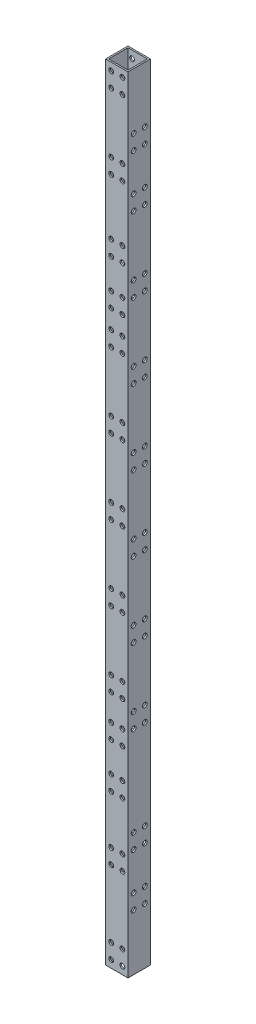
SolidWorks part; units mm, degrees
ref_plane "前视基准面" through (0, 0, 0) normal (0, 0, 1) x (1, 0, 0)
ref_plane "上视基准面" through (0, 0, 0) normal (0, 1, 0) x (1, 0, 0)
ref_plane "右视基准面" through (0, 0, 0) normal (1, 0, 0) x (0, 0, -1)
other "Configuration Table"
sketch "草图1" plane through (0, 0, 0) normal (0, 1, 0) x (1, 0, 0)
  line L1 (6.5, -6.5) -> (-6.5, -6.5)
  line L2 (6.5, -6.5) -> (6.5, 6.5)
  line L3 (6.5, 6.5) -> (-6.5, 6.5)
  line L4 (-6.5, -6.5) -> (-6.5, 6.5)
  line L5 (6.5, -6.5) -> (-6.5, 6.5) construction
  line L6 (6.5, 6.5) -> (-6.5, -6.5) construction
  line L7 (7.5, -7.5) -> (-7.5, -7.5)
  line L8 (7.5, -7.5) -> (7.5, 7.5)
  line L9 (7.5, 7.5) -> (-7.5, 7.5)
  line L10 (-7.5, -7.5) -> (-7.5, 7.5)
  line L11 (7.5, -7.5) -> (-7.5, 7.5) construction
  line L12 (7.5, 7.5) -> (-7.5, -7.5) construction
  point P0 (0, 0)
  point P6 (0, 0)
  dimension "D1" = 15
  dimension "D2" = 13
extrude "凸台-拉伸1" add sketch "草图1" along normal blind 525
sketch "草图2" plane through (0, 0, 7.5) normal (0, 0, 1) x (1, 0, 0)
  line L0 (0, 804.3358) -> (0, 762.8538) construction
  line L1 (-7.5, 465) -> (7.5, 465) construction
  line L2 (-7.5, 525) -> (-7.5, 0) construction
  line L3 (7.5, 525) -> (7.5, 0) construction
  line L4 (-7.5, 525) -> (7.5, 525) construction
  line L5 (-7.5, 262.5) -> (7.5, 262.5) construction
  line L6 (-7.5, 402.5) -> (7.5, 402.5) construction
  line L7 (-7.5, 515) -> (7.5, 515) construction
  line L8 (-7.5, 10) -> (7.5, 10) construction
  line L9 (-7.5, 417.5) -> (7.5, 417.5) construction
  line L10 (-7.5, 387.5) -> (7.5, 387.5) construction
  line L11 (-7.5, 137.5) -> (7.5, 137.5) construction
  line L12 (-7.5, 107.5) -> (7.5, 107.5) construction
  line L13 (-7.5, 122.5) -> (7.5, 122.5) construction
  circle A9 centre (3.75, 520) radius 1.6
  circle A11 centre (-3.75, 520) radius 1.6
  circle A12 centre (-3.75, 510) radius 1.6
  circle A13 centre (3.75, 510) radius 1.6
  circle A14 centre (3.75, 15) radius 1.6
  circle A15 centre (-3.75, 15) radius 1.6
  circle A16 centre (-3.75, 5) radius 1.6
  circle A17 centre (3.75, 5) radius 1.6
  circle A18 centre (-3.75, 470) radius 1.6
  circle A19 centre (3.75, 470) radius 1.6
  circle A20 centre (3.75, 460) radius 1.6
  circle A21 centre (-3.75, 460) radius 1.6
  circle A26 centre (-3.75, 370) radius 1.6
  circle A27 centre (3.75, 370) radius 1.6
  circle A28 centre (3.75, 360) radius 1.6
  circle A29 centre (-3.75, 360) radius 1.6
  circle A30 centre (-3.75, 320) radius 1.6
  circle A31 centre (3.75, 320) radius 1.6
  circle A32 centre (3.75, 310) radius 1.6
  circle A33 centre (-3.75, 310) radius 1.6
  circle A34 centre (-3.75, 270) radius 1.6
  circle A35 centre (3.75, 270) radius 1.6
  circle A36 centre (3.75, 260) radius 1.6
  circle A37 centre (-3.75, 260) radius 1.6
  circle A38 centre (-3.75, 220) radius 1.6
  circle A39 centre (3.75, 220) radius 1.6
  circle A40 centre (3.75, 210) radius 1.6
  circle A41 centre (-3.75, 210) radius 1.6
  circle A42 centre (-3.75, 170) radius 1.6
  circle A43 centre (3.75, 170) radius 1.6
  circle A44 centre (3.75, 160) radius 1.6
  circle A45 centre (-3.75, 160) radius 1.6
  circle A50 centre (-3.75, 70) radius 1.6
  circle A51 centre (3.75, 70) radius 1.6
  circle A52 centre (3.75, 60) radius 1.6
  circle A53 centre (-3.75, 60) radius 1.6
  circle A54 centre (-3.75, 420) radius 1.6 [skipped]
  circle A55 centre (3.75, 420) radius 1.6 [skipped]
  circle A56 centre (-3.75, 410) radius 1.6 [skipped]
  circle A57 centre (3.75, 410) radius 1.6 [skipped]
  circle A58 centre (-3.75, 422.5) radius 1.6
  circle A59 centre (3.75, 422.5) radius 1.6
  circle A60 centre (3.75, 412.5) radius 1.6
  circle A61 centre (-3.75, 412.5) radius 1.6
  circle A62 centre (-3.75, 392.5) radius 1.6
  circle A63 centre (3.75, 392.5) radius 1.6
  circle A64 centre (3.75, 382.5) radius 1.6
  circle A65 centre (-3.75, 382.5) radius 1.6
  circle A66 centre (-3.75, 142.5) radius 1.6
  circle A67 centre (3.75, 142.5) radius 1.6
  circle A68 centre (3.75, 132.5) radius 1.6
  circle A69 centre (-3.75, 132.5) radius 1.6
  circle A70 centre (-3.75, 112.5) radius 1.6
  circle A71 centre (3.75, 112.5) radius 1.6
  circle A72 centre (3.75, 102.5) radius 1.6
  circle A73 centre (-3.75, 102.5) radius 1.6
  circle A74 centre (-3.75, 120) radius 1.6 [skipped]
  circle A75 centre (3.75, 120) radius 1.6 [skipped]
  circle A76 centre (-3.75, 110) radius 1.6 [skipped]
  circle A77 centre (3.75, 110) radius 1.6 [skipped]
  point P27 (-3.75, 423.2127)
  dimension "D2" = 5
  dimension "D5" = 10
  dimension "D8" = 3.75
  dimension "D6" = 3.2
  dimension "D1" = 3.75
  dimension "D4" = 3.2
  dimension "D12" = 3.2
  dimension "D3" = 50
  dimension "D9" = 9
  dimension "D7" = 5
  dimension "D10" = 50
  dimension "D11" = 122.5
  dimension "D13" = 3.75
  dimension "D14" = 15
  dimension "D15" = 5
extrude "切除-拉伸1" cut sketch "草图2" against normal up to surface (15 mm away) up to face at (0, 262.5, -7.5)
sketch "草图3" plane through (-7.5, 0, 0) normal (-1, 0, 0) x (0, 0, 1)
  line L0 (0, 809.7886) -> (0, 782.9032) construction
  line L1 (-7.5, 482.5) -> (7.5, 482.5) construction
  line L2 (-7.5, 525) -> (-7.5, 0) construction
  line L3 (7.5, 525) -> (7.5, 0) construction
  line L4 (-7.5, 525) -> (7.5, 525) construction
  line L5 (-7.5, 465) -> (7.5, 465) construction
  line L6 (7.5, 262.5) -> (-7.5, 262.5) construction
  line L7 (-7.5, 447.5) -> (7.5, 447.5) construction
  line L8 (-7.5, 77.5) -> (7.5, 77.5) construction
  line L9 (-7.5, 60) -> (7.5, 60) construction
  line L10 (-7.5, 42.5) -> (7.5, 42.5) construction
  line L11 (-7.5, 397.5) -> (7.5, 397.5) construction
  circle A0 centre (-3.75, 487.5) radius 1.6
  circle A1 centre (3.75, 487.5) radius 1.6
  circle A2 centre (-3.75, 477.5) radius 1.6
  circle A3 centre (3.75, 477.5) radius 1.6
  circle A68 centre (3.75, 452.5) radius 1.6
  circle A69 centre (-3.75, 452.5) radius 1.6
  circle A70 centre (3.75, 442.5) radius 1.6
  circle A71 centre (-3.75, 442.5) radius 1.6
  circle A72 centre (-3.75, 82.5) radius 1.6
  circle A73 centre (3.75, 82.5) radius 1.6
  circle A74 centre (-3.75, 72.5) radius 1.6
  circle A75 centre (3.75, 72.5) radius 1.6
  circle A76 centre (3.75, 47.5) radius 1.6
  circle A77 centre (-3.75, 47.5) radius 1.6
  circle A78 centre (3.75, 37.5) radius 1.6
  circle A79 centre (-3.75, 37.5) radius 1.6
  circle A80 centre (-3.75, 402.5) radius 1.6
  circle A81 centre (3.75, 402.5) radius 1.6
  circle A82 centre (3.75, 392.5) radius 1.6
  circle A83 centre (-3.75, 392.5) radius 1.6
  circle A84 centre (-3.75, 352.5) radius 1.6
  circle A85 centre (3.75, 352.5) radius 1.6
  circle A86 centre (3.75, 342.5) radius 1.6
  circle A87 centre (-3.75, 342.5) radius 1.6
  circle A88 centre (-3.75, 302.5) radius 1.6
  circle A89 centre (3.75, 302.5) radius 1.6
  circle A90 centre (3.75, 292.5) radius 1.6
  circle A91 centre (-3.75, 292.5) radius 1.6
  circle A92 centre (-3.75, 252.5) radius 1.6
  circle A93 centre (3.75, 252.5) radius 1.6
  circle A94 centre (3.75, 242.5) radius 1.6
  circle A95 centre (-3.75, 242.5) radius 1.6
  circle A96 centre (-3.75, 202.5) radius 1.6
  circle A97 centre (3.75, 202.5) radius 1.6
  circle A98 centre (3.75, 192.5) radius 1.6
  circle A99 centre (-3.75, 192.5) radius 1.6
  circle A100 centre (-3.75, 152.5) radius 1.6
  circle A101 centre (3.75, 152.5) radius 1.6
  circle A102 centre (3.75, 142.5) radius 1.6
  circle A103 centre (-3.75, 142.5) radius 1.6
  dimension "D2" = 3.2
  dimension "D5" = 60
  dimension "D6" = 3.2
  dimension "D1" = 17.5
  dimension "D3" = 7.5
  dimension "D4" = 10
  dimension "D7" = 3.75
  dimension "D8" = 5
  dimension "D9" = 50
  dimension "D11" = 40
  dimension "D10" = 6
extrude "切除-拉伸2" cut sketch "草图3" against normal up to surface (15 mm away) up to face at (7.5, 262.5, 0)
